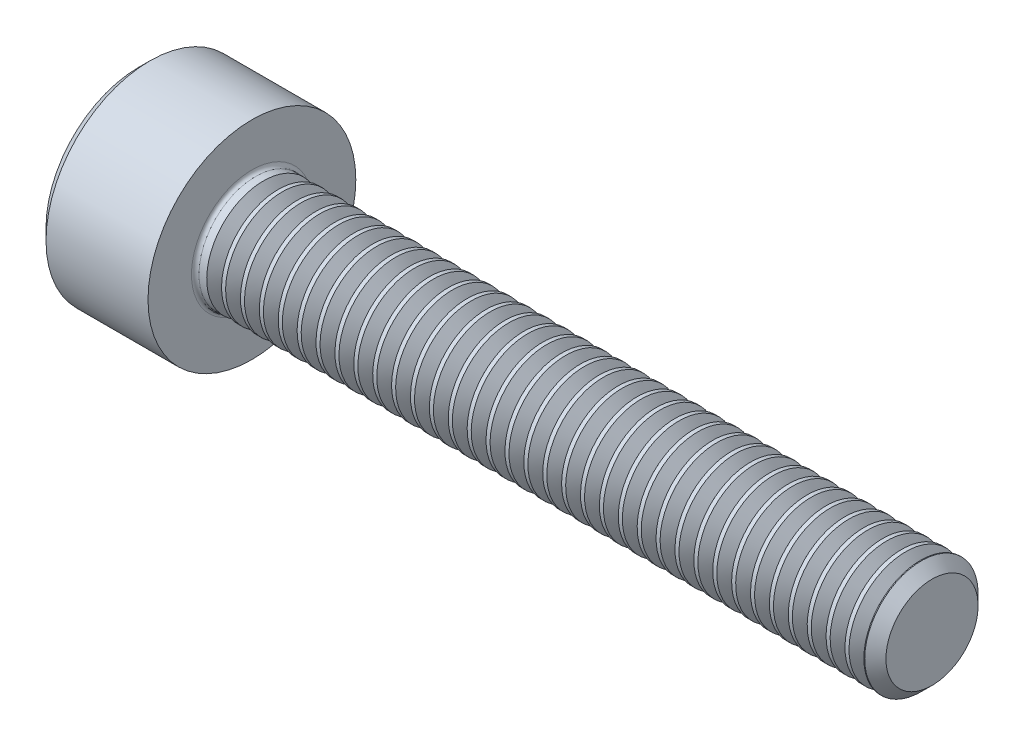
SolidWorks part; units mm, degrees
revolve "Base-Revolve" add sketch "BodySke"
sketch "BodySke" plane through (0, 0, 0) normal (0, 0, 1) x (1, 0, 0)
  line L0 (0, 0) -> (0, 2.45)
  line L1 (0.3, 2.75) -> (3, 2.75)
  line L2 (3, 2.75) -> (3, 1.5)
  line L3 (3, 1.5) -> (20.7195, 1.5)
  line L4 (21, 1.2195) -> (21, 0)
  line L5 (21, 0) -> (0, 0)
  line L6 (-31.75, 0) -> (127, 0) construction
  line L7 (0, 2.45) -> (0.3, 2.75)
  line L8 (21, 1.2195) -> (20.7195, 1.5)
  line L9 (0, -2.45) -> (0.3, -2.75) construction
  line L10 (21, -1.2195) -> (20.7195, -1.5) construction
  line L11 (3.5, 9.525) -> (3.5, 3.175) construction
  line L12 (3, 9.525) -> (3, 3.175) construction
  line L13 (-29, 9.525) -> (-29, 3.175) construction
  dimension "Diameter" = 3
  dimension "Head_ht" = 3
  dimension "Length" = 18
  dimension "Body_ch_ang" = 45
  dimension "Head_dia" = 5.5
  dimension "Head_ch_ang" = 45
  dimension "Minor_dia" = 2.439
  dimension "Advance" = 0.5
  dimension "Thread_nom" = 18
  dimension "Thread_length" = 50
  dimension "Head_ch_ht" = 0.3
cosmetic thread "ThreadCosmetic" [suppressed]
fillet "Fillet1" radius 0.1 1 edges at (3, 0, 1.5)
ref_plane "Plane1" through (0, 0, 0) normal (0, 0, 1) x (1, 0, 0)
ref_plane "Plane2" through (0, 0, 0) normal (0, 1, 0) x (1, 0, 0)
ref_plane "Plane3" through (0, 0, 0) normal (1, 0, 0) x (0, 0, -1)
sketch "Sketch2" plane through (0, 0, 0) normal (0, 0, 1) x (1, 0, 0)
  line L0 (0, 1.28) -> (1.3, 1.28)
  line L1 (1.3, 1.28) -> (2.039, 0)
  line L2 (-31.75, 0) -> (127, 0) construction
  line L3 (2.039, 0) -> (0, 0)
  line L4 (0, 0) -> (0, 1.28)
  line L5 (0, 2.45) -> (0, -2.45) construction
  line L6 (0, 0) -> (47.625, 0) construction
  line L7 (3, -2.75) -> (3, 2.75) construction
  dimension "D1" = 1.28
  dimension "D2" = 60
revolve "Hex-PreBroach" cut sketch "Sketch2" angle 360 about L6
sketch "Sketch3" plane through (0, 0, 0) normal (-1, 0, 0) x (0, 0.5, 0.866)
  line L0 (0.739, 1.28) -> (-0.739, 1.28)
  line L1 (-0.739, 1.28) -> (-1.478, 0)
  line L2 (0.739, 1.28) -> (1.478, 0)
  line L3 (0.739, -1.28) -> (1.478, 0)
  line L4 (0.739, -1.28) -> (-0.739, -1.28)
  line L5 (-0.739, -1.28) -> (-1.478, 0)
  dimension "D1" = 1.28
  dimension "D2" = 1.28
  dimension "Hex_size" = 2.56
extrude "Hex" cut sketch "Sketch3" against normal blind 1.3
sketch "Sketch4" plane through (0, 0, 0) normal (-1, 0, 0) x (0, 0, 1)
  line L0 (0, 0) -> (1.4605, 0)
  line L1 (0, 0) -> (6.1484, 3.5498) construction
  line L2 (0, 0) -> (0.7302, 1.2648)
  line L3 (1.2009, 0.3267) -> (1.3933, 0.4378)
  line L4 (0.8834, 0.8767) -> (1.0758, 0.9877)
  arc A0 (1.2009, 0.3267) -> (0.8834, 0.8767) centre (0, 0) ccw
  arc A1 (1.4605, 0) -> (1.3933, 0.4378) centre (0, 0) ccw
  arc A2 (0.7302, 1.2648) -> (1.0758, 0.9877) centre (0, 0) cw
  dimension "D1" = 30
  dimension "D2" = 60
  dimension "Spline_p_dim" = 0.635
  dimension "D3" = 0.3175
extrude "Spline" [suppressed] cut sketch "Sketch4" against normal blind 1.3
pattern_circular "CirPattern1" [suppressed] count 6 every 60
sketch "Sketch5" plane through (0, 0, 0) normal (0, 0, 1) x (1, 0, 0)
  line L0 (-31.75, 0) -> (127, 0) construction
  line L2 (0, 2.45) -> (0, -2.45) construction
  circle A0 centre (1.2, 0) radius 0.475
  dimension "Drilled_hole_dia" = 0.95
  dimension "Drilled_hole_loc" = 1.2
extrude "Hole" [suppressed] cut sketch "Sketch5" against normal through all and the other way through all
pattern_circular "Drilled-4" [suppressed] count 2 every 60
pattern_circular "Drilled-6" [suppressed] count 3 every 60
sketch "ThdSchSke" plane through (0, 0, 0) normal (0, 0, 1) x (1, 0, 0)
  line L0 (3.5, -1.2195) -> (3.3036, -1.5)
  line L1 (3.5, -1.2195) -> (3.6964, -1.5)
  line L2 (3.6964, -1.5) -> (3.6964, -1.875)
  line L3 (-3.175, 0) -> (5.1513, 0) construction
  line L5 (3.6964, -1.875) -> (3.3036, -1.875)
  line L6 (3.3036, -1.875) -> (3.3036, -1.5)
  line L7 (0, 2.45) -> (0, -2.45) construction
  dimension "Thread_minor" = 2.439
  dimension "Diameter" = 3
  dimension "Start" = 3.5
revolve "ThreadSchematic" cut sketch "ThdSchSke" angle 360 about L3
pattern_linear "ThdSchPat" count 35 spacing 0.5 along (1, 0, 0) of "ThreadSchematic"
equation "\"D2@Sketch3\" = \"Hex_size@Sketch3\" / 2"
equation "\"D1@Sketch3\" = \"Hex_size@Sketch3\" / 2"
equation "\"D1@Sketch2\" = \"Hex_size@Sketch3\" / 2"
equation "\"D3@Sketch4\" = \"Spline_p_dim@Sketch4\" / 2"
equation "\"Thread_minor@ThreadCosmetic\"  =  \"Minor_dia@BodySke\""
equation "\"D2@CirPattern1\" = 360 / \"Num_teeth@CirPattern1\""
equation "\"Wall_thickness@Sketch2\" = \"Head_ht@BodySke\" - \"Key_eng@Hex\""
equation "\"Thread_length@ThreadCosmetic\" = ((sgn( (\"Length@BodySke\" - \"Advance@BodySke\" ) - \"Thread_nom@BodySke\" )-1)*( (\"Length@BodySke\" - \"Advance@BodySke\" ) - \"Thread_nom@BodySke\" ))/-2+ \"Thread_nom@BodySke\""
equation "\"Thread_minor@ThdSchSke\" = \"Minor_dia@BodySke\""
equation "\"Diameter@ThdSchSke\" = \"Diameter@BodySke\""
equation "\"Overcut@ThdSchSke\" = \"Diameter@BodySke\" * 1.25"
equation "\"Start@ThdSchSke\" = \"Head_ht@BodySke\" + \"Length@BodySke\" - \"Thread_length@ThreadCosmetic\"  '---Non-countersunk---"
equation "\"Num_threads@ThdSchPat\" = int( \"Thread_length@ThreadCosmetic\" / \"Advance@BodySke\" + 0.999 )  + 1"
equation "\"Advance@ThdSchPat\" = \"Thread_length@ThreadCosmetic\" /  (\"Num_threads@ThdSchPat\" - 1) 'relax it"
equation "\"Num_threads@ThdSchPat\" = \"Num_threads@ThdSchPat\" - sgn( \"Num_threads@ThdSchPat\" - 1) '---chamfered tips only---"
